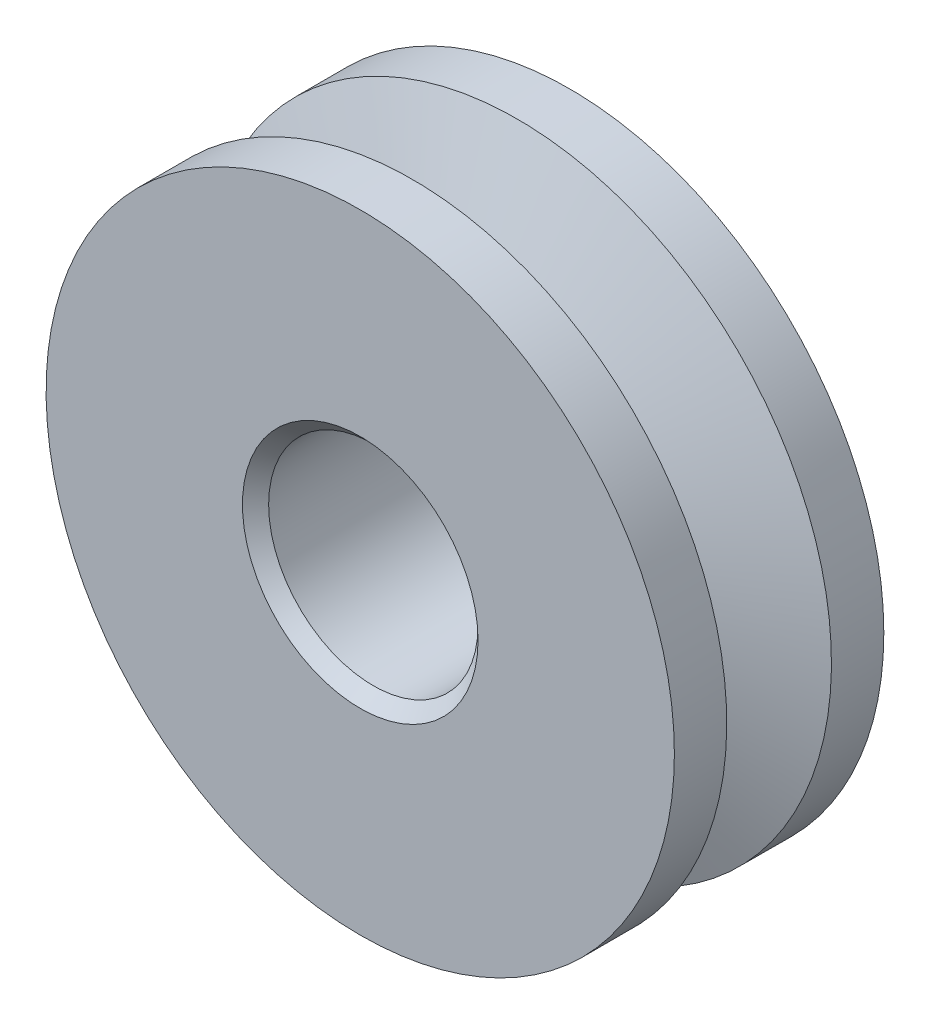
SolidWorks part; units mm, degrees
ref_plane "Front Plane" through (0, 0, 0) normal (0, 0, 1) x (1, 0, 0)
ref_plane "Top Plane" through (0, 0, 0) normal (0, 1, 0) x (1, 0, 0)
ref_plane "Right Plane" through (0, 0, 0) normal (1, 0, 0) x (0, 0, -1)
sketch "Sketch1" plane through (0, 0, 0) normal (0, 0, 1) x (1, 0, 0)
  circle A0 centre (0, 0) radius 19.05
  circle A1 centre (0, 0) radius 6.35
  dimension "D1" = 38.1
  dimension "D2" = 12.7
extrude "Extrude1" add sketch "Sketch1" along normal mid plane 12.7
sketch "Sketch2" plane through (0, 0, 0) normal (1, 0, 0) x (0, 0, -1)
  line L0 (-3.175, 19.05) -> (3.175, 19.05)
  line L2 (3.175, 19.05) -> (0.8638, 12.7)
  line L3 (0.8638, 12.7) -> (-0.8638, 12.7)
  line L4 (-0.8638, 12.7) -> (-3.175, 19.05)
  line L5 (-6.35, 0) -> (6.35, 0) construction
  line L6 (-6.35, 19.05) -> (-6.35, -19.05) construction
  line L7 (6.35, -19.05) -> (6.35, 19.05) construction
  point P2 (0, 19.05)
  point P5 (0, 12.7)
  dimension "D1" = 19.05
  dimension "D2" = 6.35
  dimension "D3" = 6.35
  dimension "D4" = 40
chamfer "Chamfer1" distance 0.7937 angle 45 2 edges at (6.35, 0, -6.35) (6.35, 0, 6.35)
revolve "Cut-Revolve1" cut sketch "Sketch2" angle 360 about L5
